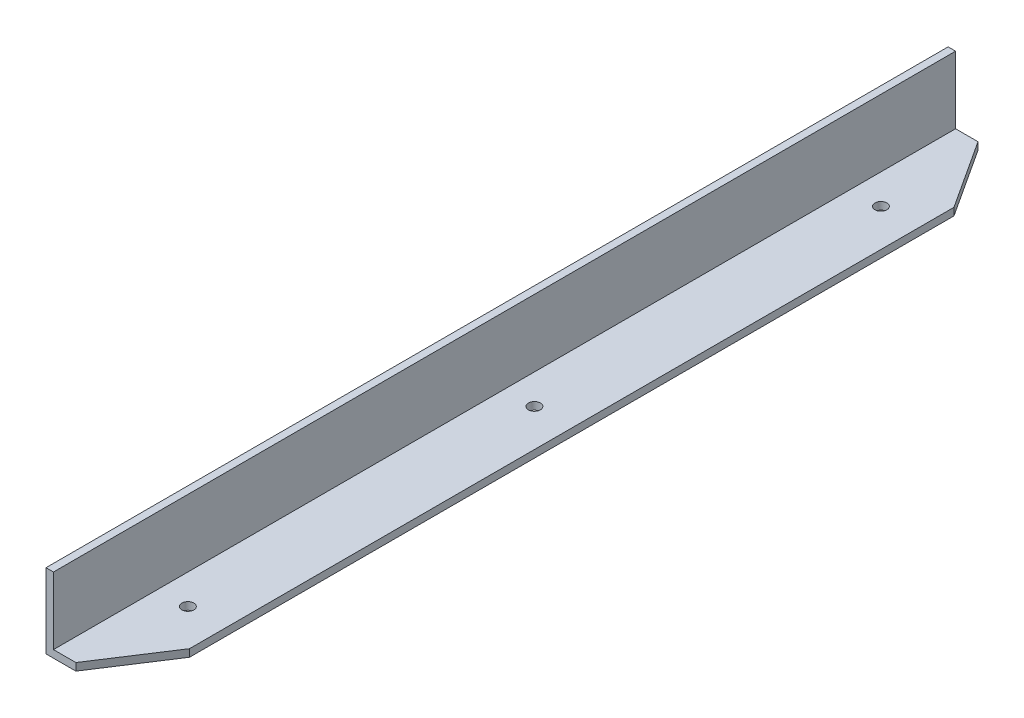
SolidWorks part; units mm, degrees
material "ASTM A36 Steel"
ref_plane "Front Plane" through (0, 0, 0) normal (0, 0, 1) x (1, 0, 0)
ref_plane "Top Plane" through (0, 0, 0) normal (0, 1, 0) x (1, 0, 0)
ref_plane "Right Plane" through (0, 0, 0) normal (1, 0, 0) x (0, 0, -1)
sketch "Sketch1" plane through (0, 0, 0) normal (0, 0, 1) x (1, 0, 0)
  line L0 (-16.7251, 34.538) -> (-11.7251, 34.538)
  line L1 (-11.7251, 34.538) -> (-11.7251, -10.462)
  line L2 (-11.7251, -10.462) -> (33.2749, -10.462)
  line L3 (33.2749, -10.462) -> (33.2749, -15.462)
  line L4 (33.2749, -15.462) -> (-16.7251, -15.462)
  line L5 (-16.7251, -15.462) -> (-16.7251, 34.538)
  dimension "D1" = 50
  dimension "D2" = 50
  dimension "D3" = 5
  dimension "D4" = 5
extrude "Boss-Extrude1" add sketch "Sketch1" along normal mid plane 604.02
sketch "Sketch2" plane through (0, -10.462, 0) normal (0, 1, 0) x (1, 0, 0)
  line L1 (33.2749, -302.01) -> (33.2749, 302.01) construction
  line L2 (33.2749, 302.01) -> (-11.7251, 302.01) construction
  circle A0 centre (8.2749, 232.01) radius 4
  dimension "D1" = 8
  dimension "D3" = 70
  dimension "10" = 25
extrude "Cut-Extrude1" cut sketch "Sketch2" against normal blind 20
sketch "Sketch3" plane through (0, -10.462, 0) normal (0, 1, 0) x (1, 0, 0)
  line L0 (33.2749, 255.9123) -> (3.2749, 302.01)
  line L1 (33.2749, -302.01) -> (33.2749, 302.01) construction
  line L2 (33.2749, 302.01) -> (-11.7251, 302.01) construction
  line L3 (3.2749, 302.01) -> (33.2749, 302.01)
  line L4 (33.2749, 302.01) -> (33.2749, 255.9123)
  dimension "D1" = 55
  dimension "D2" = 30
extrude "Cut-Extrude2" cut sketch "Sketch3" against normal blind 8
mirror "Mirror2" about plane through (0, 0, 0) normal (0, 0, 1) of "Cut-Extrude2"
pattern_linear "LPattern1" count 3 spacing 232.01 along (0, 0, 1) of "Cut-Extrude1"
